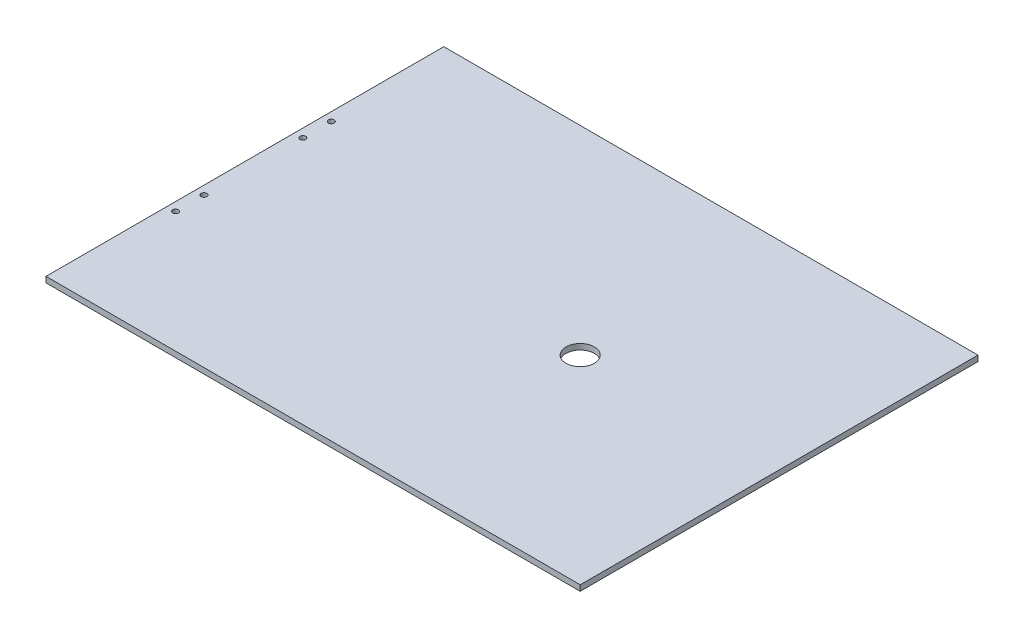
SolidWorks part; units mm, degrees
ref_plane "Front Plane" through (0, 0, 0) normal (0, 0, 1) x (1, 0, 0)
ref_plane "Top Plane" through (0, 0, 0) normal (0, 1, 0) x (1, 0, 0)
ref_plane "Right Plane" through (0, 0, 0) normal (1, 0, 0) x (0, 0, -1)
sketch "Sketch6" plane through (0, 0, 0) normal (0, 1, 0) x (1, 0, 0)
  line L1 (-175, 175) -> (175, 175)
  line L2 (-175, 175) -> (-175, -175)
  line L3 (-175, -175) -> (175, -175)
  line L4 (175, 175) -> (175, -175)
  line L5 (-175, 175) -> (175, -175) construction
  line L6 (-175, -175) -> (175, 175) construction
  circle A0 centre (0, 0) radius 12.5
extrude "Boss-Extrude1" add sketch "Sketch6" along normal blind 5
sketch "Sketch7" plane through (0, 5, 0) normal (0, 1, 0) x (1, 0, 0)
  line L1 (-175, 175) -> (-295, 175)
  line L2 (-175, 175) -> (-175, -175)
  line L3 (-175, -175) -> (-295, -175)
  line L4 (-295, 175) -> (-295, -175)
extrude "Boss-Extrude2" add sketch "Sketch7" against normal up to surface (5 mm away) up to face at (0, 0, 0)
sketch "Sketch8" plane through (0, 5, 0) normal (0, 1, 0) x (1, 0, 0)
  line L0 (-295, 36) -> (-295, -36)
  line L1 (-295, 0) -> (-287.5, 0)
  line L2 (-294.5, 76) -> (-294.5, 66)
  line L3 (-294.5, 66) -> (-295, 66)
  line L4 (-295, 66) -> (-295, 56)
  line L5 (-295, 56) -> (-294.5251, 56)
  line L6 (-294.5251, 56) -> (-294.5251, 46)
  line L7 (-294.5251, 46) -> (-295, 46)
  line L8 (-295, 46) -> (-295, 36)
  line L9 (-295, 36) -> (-280, 36)
  line L10 (-280, 36) -> (-280, 76)
  line L11 (-280, 76) -> (-294.5, 76)
  line L12 (-280, -76) -> (-294.5, -76)
  line L13 (-280, -36) -> (-280, -76)
  line L14 (-295, -36) -> (-280, -36)
  line L15 (-295, -46) -> (-295, -36)
  line L16 (-294.5251, -46) -> (-295, -46)
  line L17 (-294.5251, -56) -> (-294.5251, -46)
  line L18 (-295, -56) -> (-294.5251, -56)
  line L19 (-295, -66) -> (-295, -56)
  line L20 (-294.5, -66) -> (-295, -66)
  line L21 (-294.5, -76) -> (-294.5, -66)
  line L22 (-295, 0) -> (-278.9874, 0)
  line L23 (-295, 175) -> (-295, -175) construction
  circle A0 centre (-287.5, -68.5) radius 2.5
  circle A1 centre (-287.5, -43.5) radius 2.5
  circle A2 centre (-287.5, 43.5) radius 2.5
  circle A3 centre (-287.5, 68.5) radius 2.5
  circle A4 centre (-287.5, 68.5) radius 2.5
  circle A5 centre (-287.5, 43.5) radius 2.5
  circle A6 centre (-287.5, -43.5) radius 2.5
  circle A7 centre (-287.5, -68.5) radius 2.5
  circle A8 centre (-287.5, -68.5) radius 2.5
  circle A9 centre (-287.5, -43.5) radius 2.5
extrude "Cut-Extrude1" cut sketch "Sketch8" against normal blind 10 contours A1 | A0 | A3 | A2
